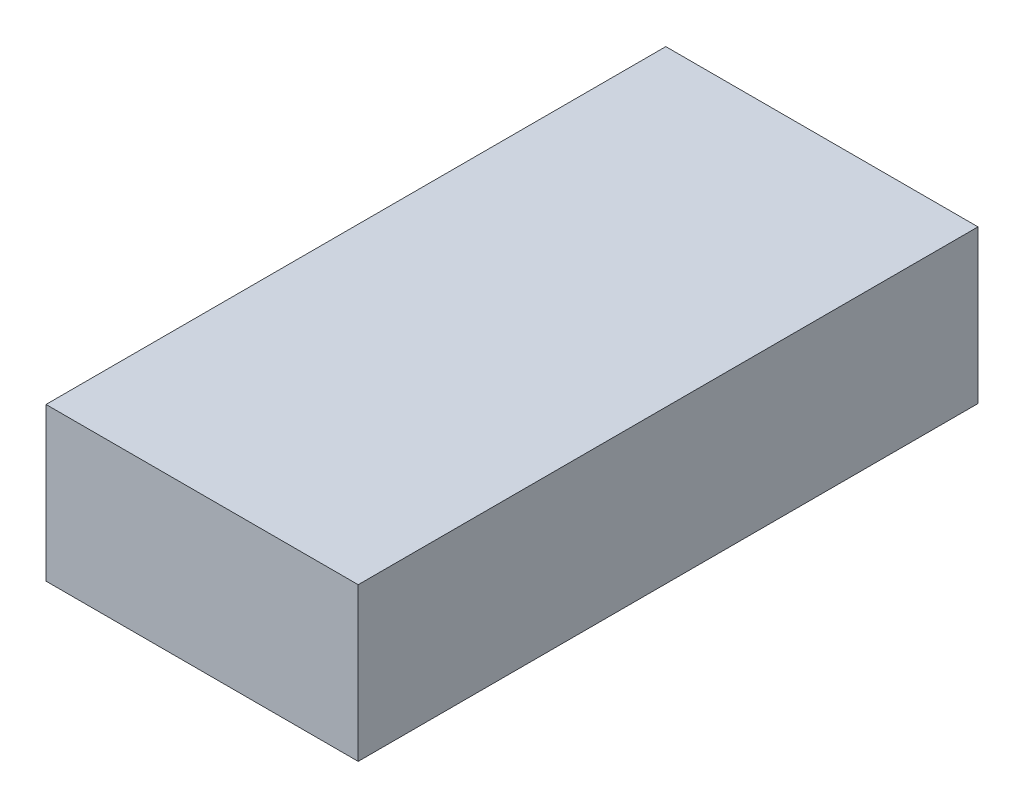
SolidWorks part; units mm, degrees
ref_plane "Front Plane" through (0, 0, 0) normal (0, 0, 1) x (1, 0, 0)
ref_plane "Top Plane" through (0, 0, 0) normal (0, 1, 0) x (1, 0, 0)
ref_plane "Right Plane" through (0, 0, 0) normal (1, 0, 0) x (0, 0, -1)
sketch "Sketch2" plane through (0, 0, 0) normal (0, 1, 0) x (1, 0, 0)
  line L1 (-12.954, -25.7175) -> (12.954, -25.7175)
  line L2 (-12.954, -25.7175) -> (-12.954, 25.7175)
  line L3 (-12.954, 25.7175) -> (12.954, 25.7175)
  line L4 (12.954, -25.7175) -> (12.954, 25.7175)
  line L5 (0, 25.7175) -> (0, -25.7175) construction
  line L6 (-12.954, 0) -> (12.954, 0) construction
  point P0 (0, 0)
  dimension "D1" = 51.435
  dimension "D2" = 25.908
extrude "Boss-Extrude1" add sketch "Sketch2" along normal mid plane 12.7
